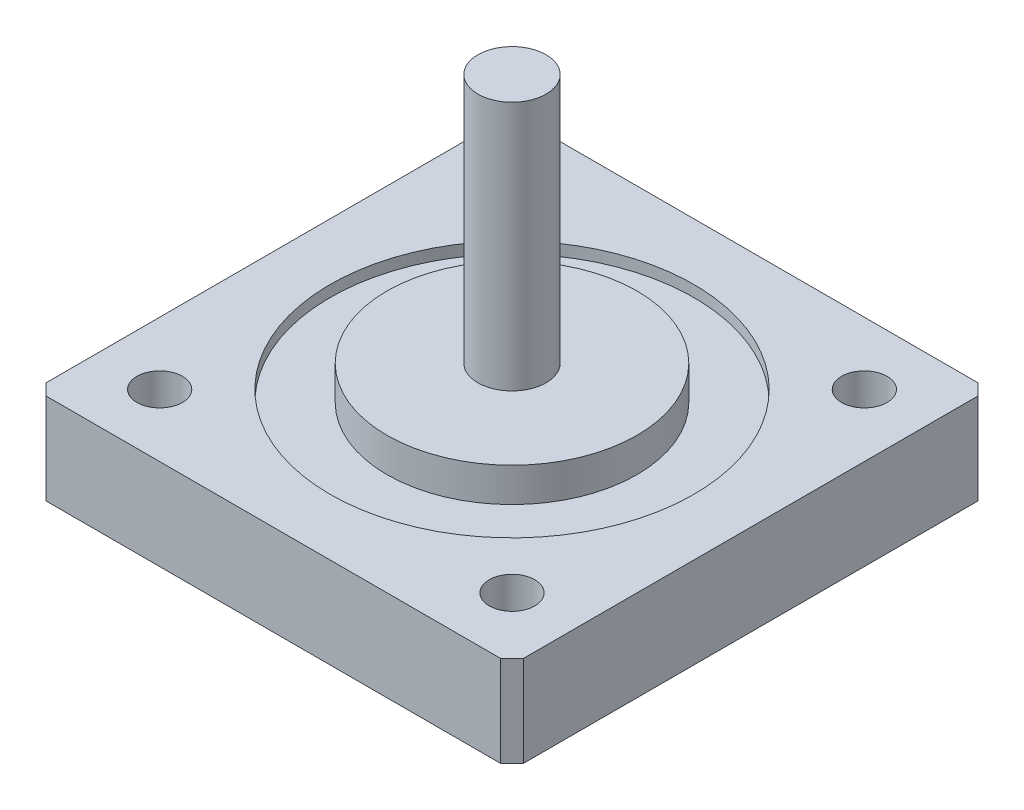
SolidWorks part; units mm, degrees
material "1060 Alloy"
ref_plane "Front Plane" through (0, 0, 0) normal (0, 0, 1) x (1, 0, 0)
ref_plane "Top Plane" through (0, 0, 0) normal (0, 1, 0) x (1, 0, 0)
ref_plane "Right Plane" through (0, 0, 0) normal (1, 0, 0) x (0, 0, -1)
sketch "Sketch1" plane through (0, 0, 0) normal (0, 1, 0) x (1, 0, 0)
  line L0 (-21, 20) -> (-20, 21)
  line L1 (-20, 21) -> (20, 21)
  line L2 (-21, 20) -> (-21, -20)
  line L3 (-20, -21) -> (20, -21)
  line L4 (21, 20) -> (21, -20)
  line L5 (-21, 21) -> (21, -21) construction
  line L6 (-21, -21) -> (21, 21) construction
  line L7 (-21, -20) -> (-20, -21)
  line L8 (20, -21) -> (21, -20)
  line L9 (20, 21) -> (21, 20)
  point P0 (0, 0)
  dimension "D1" = 42
  dimension "D2" = 42
extrude "Boss-Extrude1" add sketch "Sketch1" along normal blind 8
sketch "Sketch2" plane through (0, 8, 0) normal (0, 1, 0) x (1, 0, 0)
  circle A0 centre (0, 0) radius 11
  circle A1 centre (0, 0) radius 16
  dimension "D1" = 22
  dimension "D2" = 32
extrude "Cut-Extrude1" cut sketch "Sketch2" against normal blind 1
sketch "Sketch3" plane through (0, 8, 0) normal (0, 1, 0) x (1, 0, 0)
  circle A0 centre (0, 0) radius 3
  dimension "D1" = 6
extrude "Boss-Extrude2" add sketch "Sketch3" along normal blind 10
sketch "Sketch4" plane through (0, 8, 0) normal (0, 1, 0) x (1, 0, 0)
  circle A0 centre (-15.5, 15.5) radius 2
  circle A1 centre (15.5, 15.5) radius 2
  circle A2 centre (15.5, -15.5) radius 2
  circle A3 centre (-15.5, -15.5) radius 2
  point P0 (0, 0)
  point P11 (0, 0)
  dimension "D2" = 4
  dimension "D3" = 4
  dimension "D4" = 4
  dimension "D5" = 4
  dimension "D1" = 31
  dimension "D6" = 31
extrude "Cut-Extrude2" cut sketch "Sketch4" against normal through all
sketch "Sketch5" plane through (0, 8, 0) normal (0, 1, 0) x (1, 0, 0)
  circle A0 centre (0, 0) radius 11
  dimension "D1" = 22
extrude "Boss-Extrude4" add sketch "Sketch5" along normal blind 2
sketch "Sketch6" plane through (0, 18, 0) normal (0, 1, 0) x (1, 0, 0)
  circle A0 centre (0, 0) radius 3
extrude "Boss-Extrude5" add sketch "Sketch6" along normal blind 14
